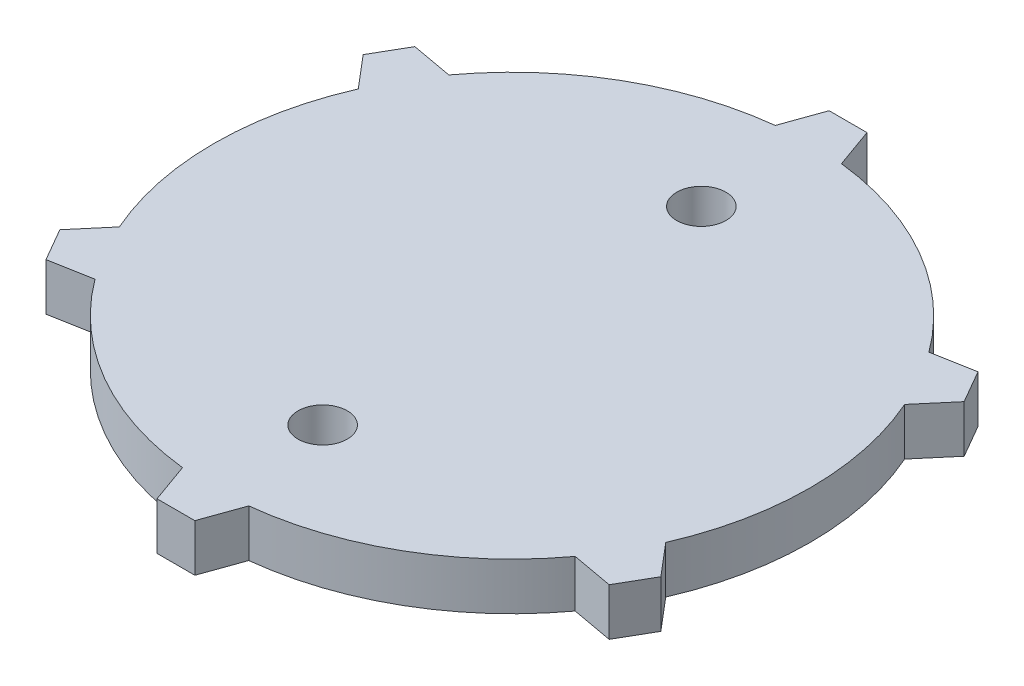
SolidWorks part; units mm, degrees
ref_plane "Front Plane" through (0, 0, 0) normal (0, 0, 1) x (1, 0, 0)
ref_plane "Top Plane" through (0, 0, 0) normal (0, 1, 0) x (1, 0, 0)
ref_plane "Right Plane" through (0, 0, 0) normal (1, 0, 0) x (0, 0, -1)
sketch "Sketch1" plane through (0, 0, 0) normal (0, 1, 0) x (1, 0, 0)
  line L0 (2, 35.5) -> (-2, 35.5)
  line L1 (0, 31.5097) -> (0, 0) construction
  line L2 (-2, 35.5) -> (-3.5, 31.305)
  line L3 (2, 35.5) -> (3.5, 31.305)
  line L4 (29.7439, 19.4821) -> (25.3609, 18.6836)
  line L5 (31.7439, 16.0179) -> (29.7439, 19.4821)
  line L6 (31.7439, 16.0179) -> (28.8609, 12.6214)
  line L7 (31.7439, -16.0179) -> (28.8609, -12.6214)
  line L8 (29.7439, -19.4821) -> (31.7439, -16.0179)
  line L9 (29.7439, -19.4821) -> (25.3609, -18.6836)
  line L10 (2, -35.5) -> (3.5, -31.305)
  line L11 (-2, -35.5) -> (2, -35.5)
  line L12 (-2, -35.5) -> (-3.5, -31.305)
  line L13 (-29.7439, -19.4821) -> (-25.3609, -18.6836)
  line L14 (-31.7439, -16.0179) -> (-29.7439, -19.4821)
  line L15 (-31.7439, -16.0179) -> (-28.8609, -12.6214)
  line L16 (-31.7439, 16.0179) -> (-28.8609, 12.6214)
  line L17 (-29.7439, 19.4821) -> (-31.7439, 16.0179)
  line L18 (-29.7439, 19.4821) -> (-25.3609, 18.6836)
  arc A5 (-28.8609, 12.6214) -> (-28.8609, -12.6214) centre (0, 0) ccw
  arc A7 (-28.8609, 12.6214) -> (-28.8609, -12.6214) centre (0, 0) ccw
  arc A8 (-28.8609, 12.6214) -> (-28.8609, -12.6214) centre (0, 0) ccw
  arc A9 (-28.8609, 12.6214) -> (-28.8609, -12.6214) centre (0, 0) ccw
  arc A10 (-28.8609, 12.6214) -> (-28.8609, -12.6214) centre (0, 0) ccw
  arc A11 (-28.8609, 12.6214) -> (-28.8609, -12.6214) centre (0, 0) ccw
  arc A12 (-3.5, 31.305) -> (-25.3609, 18.6836) centre (0, 0) ccw
  arc A13 (-3.5, 31.305) -> (-25.3609, 18.6836) centre (0, 0) ccw
  arc A14 (-3.5, 31.305) -> (-25.3609, 18.6836) centre (0, 0) ccw
  arc A15 (-3.5, 31.305) -> (-25.3609, 18.6836) centre (0, 0) ccw
  arc A16 (-3.5, 31.305) -> (-25.3609, 18.6836) centre (0, 0) ccw
  arc A17 (-3.5, 31.305) -> (-25.3609, 18.6836) centre (0, 0) ccw
  arc A18 (25.3609, 18.6836) -> (3.5, 31.305) centre (0, 0) ccw
  arc A19 (25.3609, 18.6836) -> (3.5, 31.305) centre (0, 0) ccw
  arc A20 (25.3609, 18.6836) -> (3.5, 31.305) centre (0, 0) ccw
  arc A21 (25.3609, 18.6836) -> (3.5, 31.305) centre (0, 0) ccw
  arc A22 (25.3609, 18.6836) -> (3.5, 31.305) centre (0, 0) ccw
  arc A23 (25.3609, 18.6836) -> (3.5, 31.305) centre (0, 0) ccw
  arc A24 (28.8609, -12.6214) -> (28.8609, 12.6214) centre (0, 0) ccw
  arc A25 (28.8609, -12.6214) -> (28.8609, 12.6214) centre (0, 0) ccw
  arc A26 (28.8609, -12.6214) -> (28.8609, 12.6214) centre (0, 0) ccw
  arc A27 (28.8609, -12.6214) -> (28.8609, 12.6214) centre (0, 0) ccw
  arc A28 (28.8609, -12.6214) -> (28.8609, 12.6214) centre (0, 0) ccw
  arc A29 (28.8609, -12.6214) -> (28.8609, 12.6214) centre (0, 0) ccw
  arc A30 (3.5, -31.305) -> (25.3609, -18.6836) centre (0, 0) ccw
  arc A31 (3.5, -31.305) -> (25.3609, -18.6836) centre (0, 0) ccw
  arc A32 (3.5, -31.305) -> (25.3609, -18.6836) centre (0, 0) ccw
  arc A33 (3.5, -31.305) -> (25.3609, -18.6836) centre (0, 0) ccw
  arc A34 (3.5, -31.305) -> (25.3609, -18.6836) centre (0, 0) ccw
  arc A35 (3.5, -31.305) -> (25.3609, -18.6836) centre (0, 0) ccw
  arc A36 (-25.3609, -18.6836) -> (-3.5, -31.305) centre (0, 0) ccw
  arc A37 (-25.3609, -18.6836) -> (-3.5, -31.305) centre (0, 0) ccw
  arc A38 (-25.3609, -18.6836) -> (-3.5, -31.305) centre (0, 0) ccw
  arc A39 (-25.3609, -18.6836) -> (-3.5, -31.305) centre (0, 0) ccw
  arc A40 (-25.3609, -18.6836) -> (-3.5, -31.305) centre (0, 0) ccw
  arc A41 (-25.3609, -18.6836) -> (-3.5, -31.305) centre (0, 0) ccw
  point P1 (0, 0)
  point P10 (0, 35.5)
  point P38 (0, 0)
  dimension "D1" = 63
  dimension "D2" = 6
  dimension "D5" = 35.5
  dimension "D3" = 4
  dimension "D4" = 7
extrude "Boss-Extrude1" add sketch "Sketch1" along normal blind 5
sketch "Sketch2" plane through (0, 5, 0) normal (0, 1, 0) x (1, 0, 0)
  line L0 (0, 0) -> (18.8471, 0) construction
  line L1 (0, 20) -> (0, 0) construction
  circle A0 centre (0, 20) radius 2.6
  circle A1 centre (0, -20) radius 2.6
  dimension "D1" = 5.2
  dimension "D2" = 20
extrude "Cut-Extrude1" cut sketch "Sketch2" against normal blind 5
